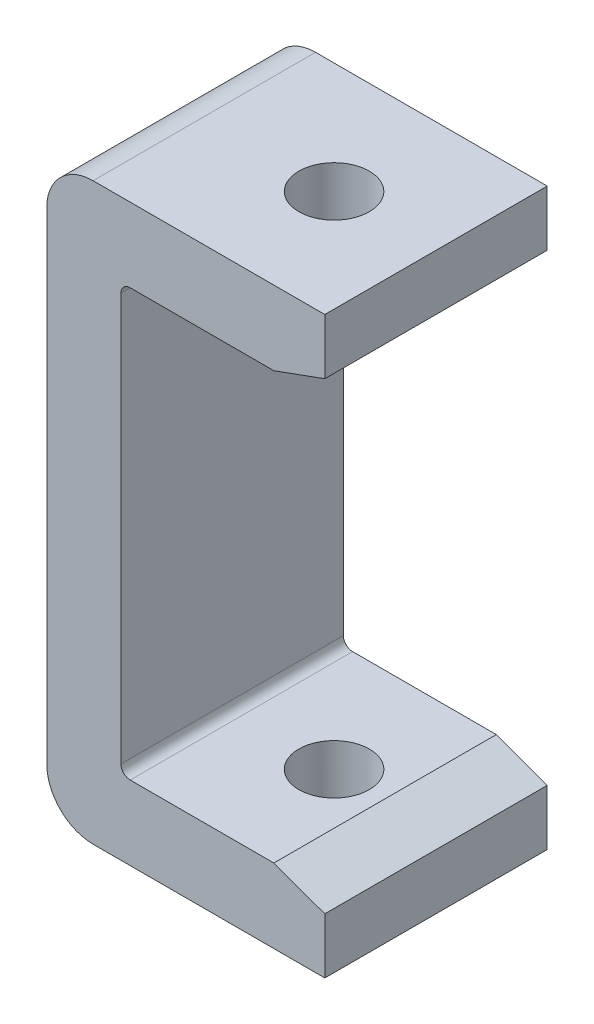
SolidWorks part; units mm, degrees
ref_plane "Alzado" through (0, 0, 0) normal (0, 0, 1) x (1, 0, 0)
ref_plane "Planta" through (0, 0, 0) normal (0, 1, 0) x (1, 0, 0)
ref_plane "Vista lateral" through (0, 0, 0) normal (1, 0, 0) x (0, 0, -1)
sketch "Croquis1" plane through (0, 0, 0) normal (0, 0, 1) x (1, 0, 0)
  line L0 (-7.5, 0) -> (-3.5, 0) construction
  line L1 (-3.5, 11.5) -> (3.5, 11.5)
  line L2 (-3.5, 11.5) -> (-3.5, -11.5)
  line L3 (-3.5, -11.5) -> (3.5, -11.5)
  line L5 (-3.5, 11.5) -> (3.5, -11.5) construction
  line L6 (-3.5, -11.5) -> (3.5, 11.5) construction
  line L7 (-7.5, 15.5) -> (7.5, 15.5)
  line L8 (-7.5, 15.5) -> (-7.5, -15.5)
  line L9 (-7.5, -15.5) -> (7.5, -15.5)
  line L10 (7.5, 15.5) -> (7.5, 11.5)
  line L11 (-7.5, 15.5) -> (7.5, -15.5) construction
  line L12 (-7.5, -15.5) -> (7.5, 15.5) construction
  line L13 (0, 11.5) -> (0, 15.5) construction
  line L14 (3.5, 11.5) -> (7.5, 11.5)
  line L15 (3.5, -11.5) -> (7.5, -11.5)
  line L16 (7.5, -11.5) -> (7.5, -15.5)
  point P0 (0, 0)
  point P6 (0, 0)
  point P15 (0, 0)
  dimension "D1" = 4
  dimension "D2" = 23
  dimension "D3" = 11
extrude "Saliente-Extruir1" add sketch "Croquis1" along normal blind 12
sketch "Croquis2" plane through (0, 15.5, 0) normal (0, 1, 0) x (1, 0, 0)
  line L0 (2, 0) -> (2, -6) construction
  line L2 (2, -6) -> (-7.5, -6) construction
  line L3 (-7.5, -12) -> (-7.5, 0) construction
  line L4 (7.5, 0) -> (-7.5, 0) construction
  line L6 (-3.5, -12) -> (-3.5, 0) construction
  line L7 (-3.5, -12) -> (-3.5, 0) construction
  line L8 (-3.5, 0) -> (2, 0) construction
  line L9 (2, 0) -> (7.5, 0) construction
  circle A0 centre (2, -6) radius 1.9
  dimension "D1" = 3.8
extrude "Cortar-Extruir1" cut sketch "Croquis2" against normal through all
fillet "Redondeo1" radius 0.5 2 edges at (-3.5, 11.5, 6) (-3.5, -11.5, 6)
fillet "Redondeo2" radius 2.5 2 edges at (-7.5, -15.5, 6) (-7.5, 15.5, 6)
chamfer "Chaflán1" distance 1 angle 70 2 edges at (7.5, -11.5, 6) (7.5, 11.5, 6)
